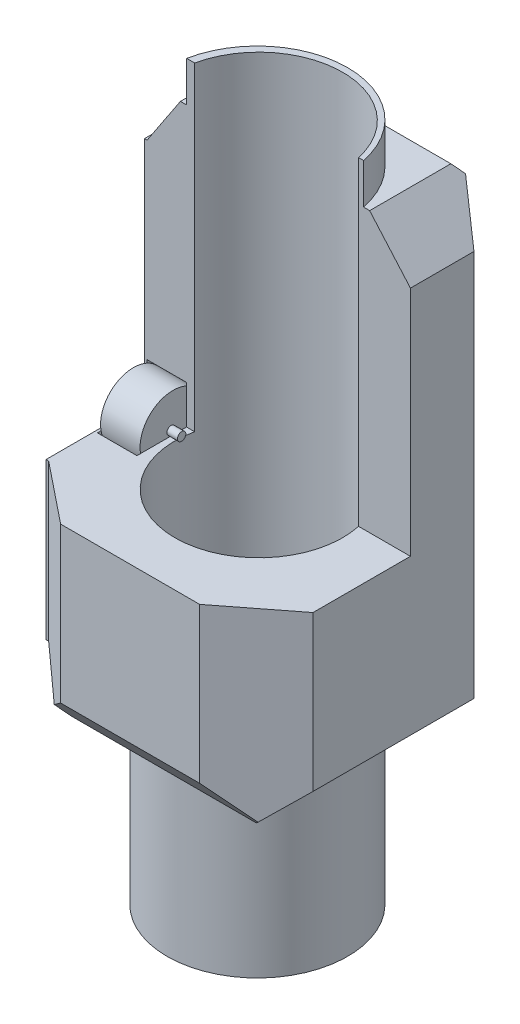
SolidWorks part; units mm, degrees
ref_plane "Front Plane" through (0, 0, 0) normal (0, 0, 1) x (1, 0, 0)
ref_plane "Top Plane" through (0, 0, 0) normal (0, 1, 0) x (1, 0, 0)
ref_plane "Right Plane" through (0, 0, 0) normal (1, 0, 0) x (0, 0, -1)
sketch "Sketch1" plane through (0, 0, 0) normal (0, 1, 0) x (1, 0, 0)
  line L1 (0, 0) -> (-100, 0)
  line L2 (0, 0) -> (0, 100)
  line L3 (0, 100) -> (-100, 100)
  line L4 (-100, 0) -> (-100, 100)
  dimension "D1" = 100
  dimension "D2" = 100
extrude "Boss-Extrude1" add sketch "Sketch1" along normal blind 180
sketch "Sketch2" plane through (0, 180, 0) normal (0, 1, 0) x (1, 0, 0)
  circle A0 centre (-51.3773, 49.0765) radius 34.2578
  point P2 (-49.1037, 52.2166)
  point P3 (-48.8771, 51.8469)
  point P4 (-51.3773, 49.0765)
extrude "Boss-Extrude2" add sketch "Sketch2" along normal mid plane 700
sketch "Sketch3" plane through (0, 0, 0) normal (1, 0, 0) x (0, 0, -1)
  line L1 (-18.5833, 361.0481) -> (133.4231, 361.0481)
  line L2 (-18.5833, 361.0481) -> (-18.5833, 643.5005)
  line L3 (-18.5833, 643.5005) -> (133.4231, 643.5005)
  line L4 (133.4231, 361.0481) -> (133.4231, 643.5005)
extrude "Cut-Extrude2" cut sketch "Sketch3" against normal blind 400
sketch "Sketch4" plane through (0, 0, 0) normal (1, 0, 0) x (0, 0, -1)
  line L0 (12.982, 0) -> (-8.9942, 25.8281)
  line L1 (-8.9942, 25.8281) -> (-18.5645, -15.2595)
  line L2 (-18.5645, -15.2595) -> (12.982, 0)
  line L3 (85.0725, -1.4481) -> (109.2376, 19.1131)
  line L4 (109.2376, 19.1131) -> (115.92, -3.2674)
  line L5 (115.92, -3.2674) -> (85.0725, -1.4481)
  line L6 (12.982, 180) -> (-8.9942, 148.5376)
  line L7 (-8.9942, 148.5376) -> (-15.4182, 193.2193)
  line L8 (-15.4182, 193.2193) -> (12.982, 180)
  line L9 (85.0725, 181.8543) -> (103.8412, 159.7959)
  line L10 (103.8412, 159.7959) -> (106.1325, 198.6474)
  line L11 (106.1325, 198.6474) -> (85.0725, 181.8543)
extrude "Cut-Extrude3" cut sketch "Sketch4" against normal blind 400
sketch "Sketch5" plane through (0, 0, 0) normal (0, 0, 1) x (1, 0, 0)
  line L0 (-85.6233, 0) -> (-106.3704, 21.4264)
  line L1 (-106.3704, 21.4264) -> (-122.2889, 3.2093)
  line L2 (-122.2889, 3.2093) -> (-93.5263, -19.8847)
  line L3 (-93.5263, -19.8847) -> (-85.6233, 0)
  line L4 (-15.695, 0) -> (0, 15.2574)
  line L5 (0, 15.2574) -> (12.1227, 15.2574)
  line L6 (12.1227, 15.2574) -> (10.5631, -19.8847)
  line L7 (10.5631, -19.8847) -> (-15.695, 0)
  line L8 (-87.1665, 180.2481) -> (-106.3704, 151.2911)
  line L9 (-106.3704, 151.2911) -> (-117.7055, 200.5011)
  line L10 (-117.7055, 200.5011) -> (-87.1665, 180.2481)
  line L11 (-15.695, 180.2481) -> (7.8338, 153.2796)
  line L12 (7.8338, 153.2796) -> (0, 193.9412)
  line L13 (0, 193.9412) -> (-15.695, 180.2481)
extrude "Cut-Extrude4" cut sketch "Sketch5" against normal blind 400
sketch "Sketch6" plane through (0, 180, 0) normal (0, 1, 0) x (1, 0, 0)
  line L1 (-112.387, 28.4004) -> (-64.2613, -10.2128)
  line L2 (-112.387, 28.4004) -> (-124.6497, -15.5119)
  line L3 (-124.6497, -15.5119) -> (-84.4064, -15.5119)
  line L4 (-64.2613, -10.2128) -> (-84.4064, -15.5119)
  line L5 (-97.0655, 135.8618) -> (-119.3755, 77.7927)
  line L6 (-97.0655, 135.8618) -> (-66.4287, 110.5752)
  line L7 (-66.4287, 110.5752) -> (-118.0433, 64.3476)
  line L8 (-119.3755, 77.7927) -> (-118.0433, 64.3476)
  line L9 (-24.6964, -21.8158) -> (11.0921, -8.9736)
  line L10 (-24.6964, -21.8158) -> (-38.5316, -11.1392)
  line L11 (-38.5316, -11.1392) -> (17.4283, 32.3938)
  line L12 (11.0921, -8.9736) -> (17.4283, 32.3938)
  line L13 (-17.4455, 140.8044) -> (35.4175, 107.2625)
  line L14 (-17.4455, 140.8044) -> (-31.7244, 103.6253)
  line L15 (-31.7244, 103.6253) -> (9.3055, 72.9964)
  line L16 (35.4175, 107.2625) -> (9.3055, 72.9964)
  point P4 (-17.4455, 140.8044)
  point P5 (-30.2763, 114.984)
  point P6 (35.4175, 107.2625)
  point P19 (-30.6265, 106.484)
  point P20 (-11.2095, 88.3109)
extrude "Cut-Extrude5" cut sketch "Sketch6" against normal blind 400
sketch "Sketch7" plane through (0, 0, 0) normal (0, 0, 1) x (1, 0, 0)
  line L1 (-146.2029, -210.0437) -> (13.9564, -210.0437)
  line L2 (-146.2029, -210.0437) -> (-146.2029, -62.6814)
  line L3 (-146.2029, -62.6814) -> (13.9564, -62.6814)
  line L4 (13.9564, -210.0437) -> (13.9564, -62.6814)
extrude "Cut-Extrude6" cut sketch "Sketch7" against normal blind 400
sketch "Sketch8" plane through (0, 0, 0) normal (0, 0, 1) x (1, 0, 0)
  line L1 (-127.1965, 251.4288) -> (20.1142, 251.4288)
  line L2 (-127.1965, 251.4288) -> (-127.1965, 413.4677)
  line L3 (-127.1965, 413.4677) -> (20.1142, 413.4677)
  line L4 (20.1142, 251.4288) -> (20.1142, 413.4677)
extrude "Cut-Extrude7" cut sketch "Sketch8" against normal blind 400
sketch "Sketch9" plane through (0, 251.4288, 0) normal (0, 1, 0) x (1, 0, 0)
  circle A0 centre (-50.809, 49.032) radius 31.8473
  point P2 (-50.6049, 49.6989)
  point P3 (-51.6378, 48.9774)
  point P4 (-50.809, 49.032)
extrude "Cut-Extrude8" cut sketch "Sketch9" against normal blind 400
sketch "Sketch10" plane through (-100, 0, 0) normal (-1, 0, 0) x (0, 0, 1)
  line L1 (-55.8114, 74.0839) -> (84.4096, 74.0839)
  line L2 (-55.8114, 74.0839) -> (-55.8114, 286.1174)
  line L3 (-55.8114, 286.1174) -> (84.4096, 286.1174)
  line L4 (84.4096, 74.0839) -> (84.4096, 286.1174)
extrude "Cut-Extrude9" cut sketch "Sketch10" against normal blind 400
sketch "Sketch11" plane through (-100, 0, 0) normal (-1, 0, 0) x (0, 0, 1)
  circle A0 centre (-50.4133, 76.2646) radius 13.6031
  point P2 (-50.4133, 76.2646)
extrude "Cut-Extrude11" cut sketch "Sketch11" against normal blind 15
sketch "Sketch12" plane through (-85, 0, 0) normal (-1, 0, 0) x (0, 0, 1)
  circle A0 centre (-50.6588, 76.2225) radius 12.4954
  point P2 (-51.6147, 75.8831)
  point P3 (-50.6588, 76.2225)
extrude "Boss-Extrude3" add sketch "Sketch12" along normal blind 15
sketch "Sketch13" plane through (-85, 0, 0) normal (1, 0, 0) x (0, 0, -1)
  circle A0 centre (49.9452, 75.9448) radius 1.5949
extrude "Boss-Extrude4" add sketch "Sketch13" along normal blind 4
sketch "Sketch14" plane through (-100, 0, 0) normal (-1, 0, 0) x (0, 0, 1)
  line L1 (-115.7243, 195.3259) -> (-14.9757, 195.3259)
  line L2 (-115.7243, 195.3259) -> (-115.7243, 305.8809)
  line L3 (-115.7243, 305.8809) -> (-14.9757, 305.8809)
  line L4 (-14.9757, 195.3259) -> (-14.9757, 305.8809)
extrude "Cut-Extrude13" cut sketch "Sketch14" against normal blind 400
sketch "Sketch15" plane through (-100, 0, 0) normal (-1, 0, 0) x (0, 0, 1)
  line L0 (-18.4618, 14.8474) -> (-80.5077, 14.8474)
  line L1 (-80.5077, 14.8474) -> (-80.5077, 160.8968)
  line L2 (-80.5077, 160.8968) -> (-55.8114, 160.8968)
  line L3 (-55.8114, 160.8968) -> (-55.8114, 74.0839)
  line L4 (-55.8114, 74.0839) -> (-18.4618, 74.0839)
  line L5 (-18.4618, 74.0839) -> (-18.4618, 14.8474)
extrude "Boss-Extrude5" add sketch "Sketch15" along normal blind 1
sketch "Sketch16" plane through (-101, 0, 0) normal (-1, 0, 0) x (0, 0, 1)
  line L1 (-51.5273, 29.9073) -> (-27.023, 29.9073)
  line L2 (-51.5273, 29.9073) -> (-51.5273, 60.3656)
  line L3 (-51.5273, 60.3656) -> (-27.023, 60.3656)
  line L4 (-27.023, 29.9073) -> (-27.023, 60.3656)
extrude "Boss-Extrude6" add sketch "Sketch16" along normal blind 5
sketch "Sketch17" plane through (-101, 0, 0) normal (-1, 0, 0) x (0, 0, 1)
  line L1 (-76.3814, 119.2079) -> (-57.7119, 119.2079)
  line L2 (-76.3814, 119.2079) -> (-76.3814, 141.6106)
  line L3 (-76.3814, 141.6106) -> (-57.7119, 141.6106)
  line L4 (-57.7119, 119.2079) -> (-57.7119, 141.6106)
extrude "Boss-Extrude7" add sketch "Sketch17" along normal blind 1
sketch "Sketch18" plane through (-102, 0, 0) normal (-1, 0, 0) x (0, 0, 1)
  line L1 (-74.0789, 127.628) -> (-69.1713, 127.628)
  line L2 (-74.0789, 127.628) -> (-74.0789, 132.7988)
  line L3 (-74.0789, 132.7988) -> (-69.1713, 132.7988)
  line L4 (-69.1713, 127.628) -> (-69.1713, 132.7988)
  line L5 (-60.3069, 127.1415) -> (-64.2884, 127.1415)
  line L6 (-60.3069, 127.1415) -> (-60.3069, 132.5929)
  line L7 (-60.3069, 132.5929) -> (-64.2884, 132.5929)
  line L8 (-64.2884, 127.1415) -> (-64.2884, 132.5929)
extrude "Boss-Extrude8" add sketch "Sketch18" along normal blind 1
sketch "Sketch19" plane through (-102, 0, 0) normal (-1, 0, 0) x (0, 0, 1)
  line L0 (-66.9765, 134.8688) -> (-73.7929, 134.8688)
  line L1 (-73.7929, 134.8688) -> (-73.7929, 134.1083)
  line L2 (-73.7929, 134.1083) -> (-74.5719, 134.1083)
  line L3 (-74.5719, 134.1083) -> (-74.5719, 140.5127)
  line L4 (-74.5719, 140.5127) -> (-73.7929, 140.5127)
  line L5 (-73.7929, 140.5127) -> (-72.166, 140.5127)
  line L6 (-66.9765, 134.8688) -> (-66.9765, 135.4972)
  line L7 (-66.9765, 135.4972) -> (-73.7929, 135.4233)
  line L8 (-73.7929, 135.4233) -> (-73.7929, 139.5456)
  line L9 (-73.7929, 139.5456) -> (-72.9212, 139.5456)
  line L10 (-72.9212, 139.5456) -> (-72.9212, 136.6931)
  line L11 (-72.166, 140.5127) -> (-72.2334, 137.4219)
  line L12 (-72.9212, 136.6931) -> (-70.7839, 136.6931)
  line L13 (-72.2334, 137.4219) -> (-71.4846, 137.4219)
  line L14 (-71.4846, 137.4219) -> (-71.4109, 140.5127)
  line L15 (-71.4109, 140.5127) -> (-69.1583, 140.5049)
  line L16 (-70.7839, 136.6931) -> (-70.7097, 139.9027)
  line L17 (-70.7097, 139.9027) -> (-70.0087, 139.9027)
  line L18 (-69.1583, 140.5049) -> (-69.1583, 137.4219)
  line L19 (-70.0087, 139.9027) -> (-70.0087, 136.6677)
  line L20 (-70.0087, 136.6677) -> (-67.49, 136.6677)
  line L21 (-69.1583, 137.4219) -> (-68.2217, 137.4219)
  line L22 (-67.49, 136.6677) -> (-67.49, 139.9027)
  line L23 (-67.49, 139.9027) -> (-66.3346, 139.9027)
  line L24 (-66.3346, 139.9027) -> (-66.3346, 136.6677)
  line L25 (-68.2217, 137.4219) -> (-68.2217, 140.5679)
  line L26 (-68.2217, 140.5679) -> (-65.4269, 140.5679)
  line L27 (-65.4269, 140.5679) -> (-65.5152, 137.4462)
  line L28 (-66.3346, 136.6677) -> (-64.0048, 136.6677)
  line L29 (-64.0048, 136.6677) -> (-64.0048, 139.9797)
  line L30 (-64.0048, 139.9797) -> (-63.0901, 139.9797)
  line L31 (-63.0901, 139.9797) -> (-63.0901, 136.6677)
  line L32 (-63.0901, 136.6677) -> (-60.6958, 136.6677)
  line L33 (-60.6958, 136.6677) -> (-60.6958, 139.9841)
  line L34 (-60.6958, 139.9841) -> (-59.6983, 139.9949)
  line L35 (-65.5152, 137.4462) -> (-64.7141, 137.4462)
  line L36 (-64.7141, 137.4462) -> (-64.7141, 140.5679)
  line L37 (-64.7141, 140.5679) -> (-62.4109, 140.5679)
  line L38 (-62.4109, 140.5679) -> (-62.4109, 137.2101)
  line L39 (-62.4109, 137.2101) -> (-61.4035, 137.2101)
  line L40 (-61.4035, 137.2101) -> (-61.4035, 140.6311)
  line L41 (-61.4035, 140.6311) -> (-58.89, 140.6311)
  line L42 (-58.89, 140.6311) -> (-58.89, 136.5955)
  line L43 (-58.89, 136.5955) -> (-59.6983, 136.5955)
  line L44 (-59.6983, 136.5955) -> (-59.6983, 139.9949)
  point P27 (-64.7141, 140.5679)
extrude "Boss-Extrude9" add sketch "Sketch19" along normal blind 1
sketch "Sketch21" plane through (-101, 0, 0) normal (-1, 0, 0) x (0, 0, 1)
  line L1 (-51.9721, 29.5069) -> (-68.2534, 29.5069)
  line L2 (-51.9721, 29.5069) -> (-51.9721, 60.2117)
  line L3 (-51.9721, 60.2117) -> (-68.2534, 60.2117)
  line L4 (-68.2534, 29.5069) -> (-68.2534, 60.2117)
extrude "Boss-Extrude10" add sketch "Sketch21" along normal blind 5
sketch "Sketch22" plane through (-102, 0, 0) normal (-1, 0, 0) x (0, 0, 1)
  line L1 (-61.0903, 132.5972) -> (-60.5286, 132.5972)
  line L2 (-61.0903, 132.5972) -> (-61.0903, 133.2011)
  line L3 (-61.0903, 133.2011) -> (-60.5286, 133.2011)
  line L4 (-60.5286, 132.5972) -> (-60.5286, 133.2011)
  line L5 (-61.425, 132.5972) -> (-61.9595, 132.5972)
  line L6 (-61.425, 132.5972) -> (-61.425, 133.2011)
  line L7 (-61.425, 133.2011) -> (-61.9595, 133.2011)
  line L8 (-61.9595, 132.5972) -> (-61.9595, 133.2011)
  line L9 (-62.3566, 132.6053) -> (-62.8933, 132.6053)
  line L10 (-62.3566, 132.6053) -> (-62.3566, 133.2011)
  line L11 (-62.3566, 133.2011) -> (-62.8933, 133.2011)
  line L12 (-62.8933, 132.6053) -> (-62.8933, 133.2011)
  line L13 (-63.2722, 132.5972) -> (-63.8273, 132.5972)
  line L14 (-63.2722, 132.5972) -> (-63.2722, 133.2011)
  line L15 (-63.2722, 133.2011) -> (-63.8273, 133.2011)
  line L16 (-63.8273, 132.5972) -> (-63.8273, 133.2011)
  line L17 (-60.5286, 127.1114) -> (-61.0903, 127.1114)
  line L18 (-60.5286, 127.1114) -> (-60.5286, 126.5079)
  line L19 (-60.5286, 126.5079) -> (-61.0903, 126.5079)
  line L20 (-61.0903, 127.1114) -> (-61.0903, 126.5079)
  line L21 (-61.425, 127.1139) -> (-61.9595, 127.1139)
  line L22 (-61.425, 127.1139) -> (-61.425, 126.5079)
  line L23 (-61.425, 126.5079) -> (-61.9595, 126.5079)
  line L24 (-61.9595, 127.1139) -> (-61.9595, 126.5079)
  line L25 (-62.3566, 127.1139) -> (-62.8685, 127.1139)
  line L26 (-62.3566, 127.1139) -> (-62.3566, 126.5079)
  line L27 (-62.3566, 126.5079) -> (-62.8685, 126.5079)
  line L28 (-62.8685, 127.1139) -> (-62.8685, 126.5079)
  line L29 (-63.2722, 127.1139) -> (-63.8273, 127.1139)
  line L30 (-63.2722, 127.1139) -> (-63.2722, 126.5079)
  line L31 (-63.2722, 126.5079) -> (-63.8273, 126.5079)
  line L32 (-63.8273, 127.1139) -> (-63.8273, 126.5079)
extrude "Boss-Extrude11" add sketch "Sketch22" along normal blind 1
